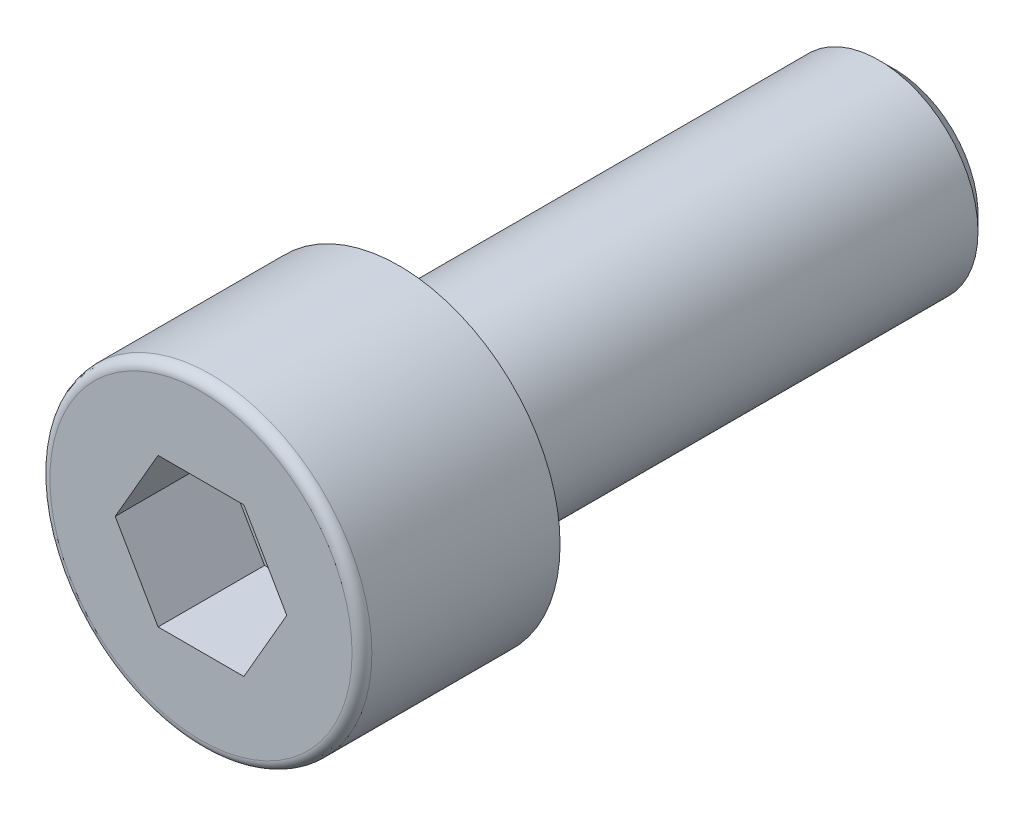
SolidWorks part; units mm, degrees
material "STAINLESS STEEL, 316S16"
ref_plane "Front Plane" through (0, 0, 0) normal (0, 0, 1) x (1, 0, 0)
ref_plane "Top Plane" through (0, 0, 0) normal (0, 1, 0) x (1, 0, 0)
ref_plane "Right Plane" through (0, 0, 0) normal (1, 0, 0) x (0, 0, -1)
sketch "Sketch1" plane through (0, 0, 0) normal (0, -1, 0) x (1, 0, 0)
  line L0 (0, 8) -> (0, -20) construction
  line L1 (0, -20) -> (-4, -20)
  line L2 (-4, -20) -> (-4, 0)
  line L3 (-4, 0) -> (-6.5, 0)
  line L4 (-6.5, 0) -> (-6.5, 7.6)
  line L5 (-6.1, 8) -> (0, 8)
  line L6 (0, 8) -> (0, -20)
  arc A0 (-6.5, 7.6) -> (-6.1, 8) centre (-6.1, 7.6) cw
  dimension "D4" = 0.4
  dimension "D1" = 8
  dimension "D2" = 13
  dimension "D3" = 8
  dimension "L" = 20
revolve "Revolve1" add sketch "Sketch1" angle 360 mid plane about L0
cosmetic thread "Thread" parameters "D1"=20, "D2"=6.619
sketch "Sketch2" plane through (0, 0, 8) normal (0, 0, 1) x (1, 0, 0)
  line L1 (3.4641, 0) -> (1.7321, 3)
  line L2 (1.7321, 3) -> (-1.7321, 3)
  line L3 (-1.7321, 3) -> (-3.4641, 0)
  line L4 (-3.4641, 0) -> (-1.7321, -3)
  line L5 (-1.7321, -3) -> (1.7321, -3)
  line L6 (1.7321, -3) -> (3.4641, 0)
  circle A0 centre (0, 0) radius 3 construction
  dimension "D1" = 6
extrude "Cut-Extrude1" cut sketch "Sketch2" against normal blind 4.3
chamfer "Chamfer1" distance 0.625 angle 45 1 edges at (4, 0, -20)
equation "\"D4@Sketch1\" = (\"D1@Sketch1\"/2)/10"
